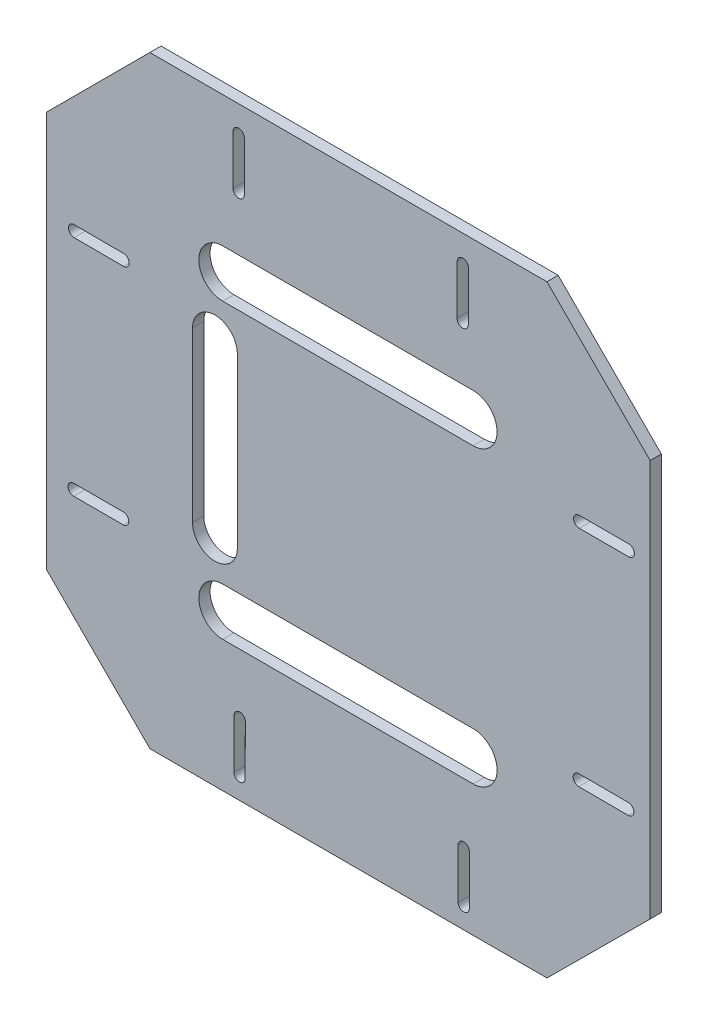
SolidWorks part; units mm, degrees
ref_plane "Front Plane" through (0, 0, 0) normal (0, 0, 1) x (1, 0, 0)
ref_plane "Top Plane" through (0, 0, 0) normal (0, 1, 0) x (1, 0, 0)
ref_plane "Right Plane" through (0, 0, 0) normal (1, 0, 0) x (0, 0, -1)
sketch "Sketch1" plane through (0, 0, 0) normal (0, 0, 1) x (1, 0, 0)
  line L0 (-73.5976, 117.2814) -> (67.8633, 117.2814)
  line L1 (-110.3672, 80.5118) -> (-110.3672, -60.7021)
  line L2 (-73.5668, -97.5025) -> (67.8941, -97.5025)
  line L3 (104.6328, 80.5118) -> (104.6328, -60.9491)
  line L5 (67.8633, 117.2814) -> (104.6328, 80.5118)
  line L7 (67.8941, -97.5025) -> (104.6328, -60.9491)
  line L8 (-110.3672, -60.7021) -> (-73.5668, -97.5025)
  line L9 (-73.5976, 117.2814) -> (-110.3672, 80.5118)
  line L10 (-106.1246, 84.7545) -> (-77.8403, 113.0387)
  line L11 (-47.6103, 62.0702) -> (41.5768, 62.0702) construction
  line L15 (-47.6103, 70.602) -> (41.5768, 70.602)
  line L16 (-47.6103, 53.5385) -> (41.5768, 53.5385)
  line L23 (-92.7181, 99.6354) -> (-92.6579, 99.6956)
  line L26 (-110.3672, 29.5608) -> (-110.3672, -10.4392)
  line L32 (-110.3672, -10.4392) -> (-110.3672, -5.1592) construction
  line L34 (-110.3672, 80.5118) -> (-110.3672, 9.9049) construction
  line L39 (-102.391, 88.488) -> (-95.6735, 81.7705)
  line L54 (-47.6103, -42.2605) -> (41.5768, -42.2605) construction
  line L55 (-47.6103, -50.7923) -> (41.5768, -50.7923)
  line L56 (-47.6103, -33.7287) -> (41.5768, -33.7287)
  line L57 (-50.4034, -20.0951) -> (-50.4034, 39.9049) construction
  line L58 (-67.9409, 117.2814) -> (-3.0009, 117.2814) construction
  line L60 (-67.9409, 117.2814) -> (-50.4034, 117.2814) construction
  line L63 (-110.3672, 39.9049) -> (-110.3672, -20.0951)
  line L64 (-58.3858, -20.0951) -> (-58.3858, 39.9049)
  line L65 (-42.4209, -20.0951) -> (-42.4209, 39.9049)
  line L66 (-41.9513, 90.1358) -> (-41.9513, 107.7809) construction
  line L67 (-43.9513, 90.1358) -> (-43.9513, 107.7809)
  line L68 (-39.9513, 90.1358) -> (-39.9513, 107.7809)
  line L71 (-33.0009, 117.2814) -> (26.9991, 117.2814)
  line L73 (-83.0981, -31.1792) -> (-100.7432, -31.1792) construction
  line L74 (37.8396, 89.9786) -> (37.9109, 107.6236) construction
  line L75 (39.8396, 89.9706) -> (39.9109, 107.6155)
  line L76 (-73.5976, 117.2814) -> (-110.3672, 80.5118)
  line L85 (35.8396, 89.9867) -> (35.9109, 107.6317)
  line L86 (-83.0981, -33.1792) -> (-100.7432, -33.1792)
  line L88 (-83.0981, -29.1792) -> (-100.7432, -29.1792)
  line L90 (-82.941, 48.6116) -> (-100.5859, 48.6829) construction
  line L91 (-82.9329, 50.6116) -> (-100.5779, 50.6829)
  line L92 (-82.9491, 46.6117) -> (-100.594, 46.683)
  line L93 (38.2169, -72.3261) -> (38.2169, -89.9712) construction
  line L94 (40.2169, -72.3261) -> (40.2169, -89.9712)
  line L95 (36.2169, -72.3261) -> (36.2169, -89.9712)
  line L96 (-41.574, -72.1689) -> (-41.6453, -89.8139) construction
  line L97 (-43.574, -72.1608) -> (-43.6453, -89.8058)
  line L98 (-39.574, -72.177) -> (-39.6453, -89.822)
  line L99 (79.3637, 48.989) -> (97.0088, 48.989) construction
  line L100 (79.3637, 50.989) -> (97.0088, 50.989)
  line L101 (79.3637, 46.989) -> (97.0088, 46.989)
  line L102 (79.2066, -30.8019) -> (96.8515, -30.8732) construction
  line L103 (79.1985, -32.8019) -> (96.8435, -32.8732)
  line L104 (79.2147, -28.8019) -> (96.8596, -28.8732)
  arc A29 (-47.6103, 70.602) -> (-47.6103, 53.5385) centre (-47.6103, 62.0702) ccw
  arc A30 (41.5768, 53.5385) -> (41.5768, 70.602) centre (41.5768, 62.0702) ccw
  arc A31 (-47.6103, -50.7923) -> (-47.6103, -33.7287) centre (-47.6103, -42.2605) cw
  arc A32 (41.5768, -33.7287) -> (41.5768, -50.7923) centre (41.5768, -42.2605) cw
  arc A33 (-58.3858, -20.0951) -> (-42.4209, -20.0951) centre (-50.4034, -20.0951) ccw
  arc A34 (-42.4209, 39.9049) -> (-58.3858, 39.9049) centre (-50.4034, 39.9049) ccw
  arc A35 (-43.9513, 90.1358) -> (-39.9513, 90.1358) centre (-41.9513, 90.1358) ccw
  arc A36 (-39.9513, 107.7809) -> (-43.9513, 107.7809) centre (-41.9513, 107.7809) ccw
  arc A37 (39.8396, 89.9706) -> (35.8396, 89.9867) centre (37.8396, 89.9786) cw
  arc A38 (35.9109, 107.6317) -> (39.9109, 107.6155) centre (37.9109, 107.6236) cw
  arc A39 (-83.0981, -33.1792) -> (-83.0981, -29.1792) centre (-83.0981, -31.1792) ccw
  arc A40 (-100.7432, -29.1792) -> (-100.7432, -33.1792) centre (-100.7432, -31.1792) ccw
  arc A41 (-82.9329, 50.6116) -> (-82.9491, 46.6117) centre (-82.941, 48.6116) cw
  arc A42 (-100.594, 46.683) -> (-100.5779, 50.6829) centre (-100.5859, 48.6829) cw
  arc A43 (40.2169, -72.3261) -> (36.2169, -72.3261) centre (38.2169, -72.3261) ccw
  arc A44 (36.2169, -89.9712) -> (40.2169, -89.9712) centre (38.2169, -89.9712) ccw
  arc A45 (-43.574, -72.1608) -> (-39.574, -72.177) centre (-41.574, -72.1689) cw
  arc A46 (-39.6453, -89.822) -> (-43.6453, -89.8058) centre (-41.6453, -89.8139) cw
  arc A47 (79.3637, 50.989) -> (79.3637, 46.989) centre (79.3637, 48.989) ccw
  arc A48 (97.0088, 46.989) -> (97.0088, 50.989) centre (97.0088, 48.989) ccw
  arc A49 (79.1985, -32.8019) -> (79.2147, -28.8019) centre (79.2066, -30.8019) cw
  arc A50 (96.8596, -28.8732) -> (96.8435, -32.8732) centre (96.8515, -30.8732) cw
  point P0 (-2.8672, 9.9049)
  point P8 (-91.9824, 99.0201)
  point P17 (-2.8672, 9.9049)
  point P18 (-91.9824, 98.8966)
  point P33 (-2.8672, 9.9049)
  point P35 (-3.0168, 62.0702)
  point P38 (-120.1149, 127.1526)
  point P41 (-120.9422, 9.9076)
  point P74 (-3.0168, -42.2605)
  point P85 (-50.4034, 9.9049)
  point P95 (-3.0168, 9.9309)
  point P97 (-41.9513, 98.9583)
  point P142 (37.8752, 98.8011)
  point P145 (-2.8672, 9.9049)
  point P152 (-91.9207, -31.1792)
  point P159 (-91.7635, 48.6473)
  point P166 (38.2169, -81.1486)
  point P173 (-41.6096, -80.9914)
  point P180 (88.1863, 48.989)
  point P187 (88.0291, -30.8376)
  point P192 (-1.8672, 8.9049)
  dimension "D19" = 2
  dimension "D20" = 4
  dimension "D22" = 2
  dimension "D1" = 52
  dimension "D2" = 141.4609
  dimension "D3" = 215
  dimension "D4" = 40
  dimension "D5" = 9.5
  dimension "D6" = 5.28
  dimension "D15" = 5.28
  dimension "D18" = 17.5375
  dimension "D21" = 64.94
extrude "Boss-Extrude2" add sketch "Sketch1" along normal blind 4
